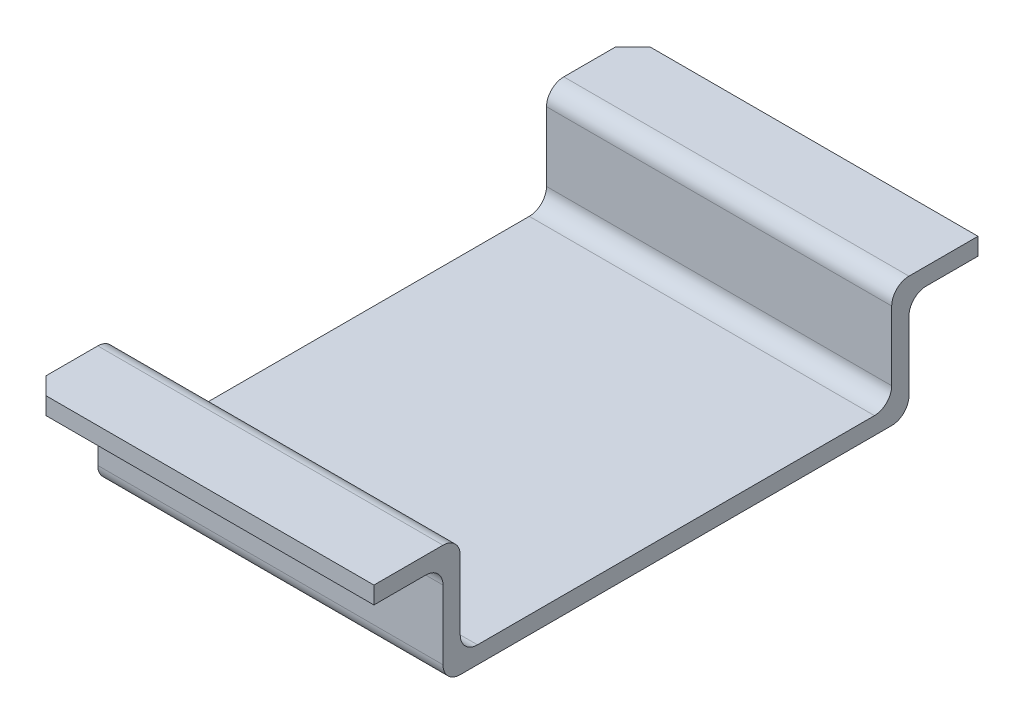
SolidWorks part; units mm, degrees
ref_plane "前视基准面" through (0, 0, 0) normal (0, 0, 1) x (1, 0, 0)
ref_plane "上视基准面" through (0, 0, 0) normal (0, 1, 0) x (1, 0, 0)
ref_plane "右视基准面" through (0, 0, 0) normal (1, 0, 0) x (0, 0, -1)
sketch "草图1" plane through (0, 0, 0) normal (1, 0, 0) x (0, 0, -1)
  line L0 (0, 0) -> (0, 32.2429) construction
  line L1 (0, 0) -> (-12.5, 0)
  line L2 (-12.5, 0) -> (-12.5, 6)
  line L3 (-12.5, 6) -> (-17.5, 6)
  line L4 (0, -1) -> (-13.5, -1)
  line L5 (-13.5, -1) -> (-13.5, 5)
  line L6 (-13.5, 5) -> (-17.5, 5)
  line L7 (0, -1) -> (13.5, -1)
  line L8 (-17.5, 6) -> (-17.5, 5)
  line L9 (0, 0) -> (12.5, 0)
  line L10 (13.5, -1) -> (13.5, 5)
  line L11 (12.5, 0) -> (12.5, 6)
  line L12 (13.5, 5) -> (17.5, 5)
  line L13 (17.5, 6) -> (17.5, 5)
  line L14 (12.5, 6) -> (17.5, 6)
  dimension "D2" = 12.5
  dimension "D3" = 6
  dimension "D4" = 17.5
  dimension "D1" = 1
extrude "凸台-拉伸1" add sketch "草图1" along normal blind 20
fillet "圆角1" radius 1 8 edges at (10, 6, 12.5) (10, 0, 12.5) (10, 5, 13.5) (10, -1, 13.5) (10, -1, -13.5) (10, 5, -13.5) (10, 6, -12.5) (10, 0, -12.5)
chamfer "倒角1" distance 1 angle 45 2 edges at (0, 5.5, 17.5) (0, 5.5, -17.5)
sketch "草图2" [suppressed] plane through (20, 0, 0) normal (1, 0, 0) x (0, 0, -1)
  line L12 (-12.5, 1) -> (-12.5, 5)
  line L13 (-13.5, 6) -> (-17.5, 6)
  line L14 (-17.5, 6) -> (-17.5, 5)
  line L15 (-17.5, 5) -> (-14.5, 5)
  line L16 (-13.5, 4) -> (-13.5, 0)
  line L17 (-12.5, -1) -> (12.5, -1)
  line L18 (13.5, 0) -> (13.5, 4)
  line L19 (14.5, 5) -> (17.5, 5)
  line L20 (17.5, 5) -> (17.5, 6)
  line L21 (17.5, 6) -> (13.5, 6)
  line L22 (12.5, 5) -> (12.5, 1)
  line L23 (11.5, 0) -> (-11.5, 0)
  line L24 (-12.5, 1) -> (-12.5, 5)
  line L25 (-13.5, 6) -> (-17.5, 6)
  line L26 (-17.5, 6) -> (-17.5, 5)
  line L27 (-17.5, 5) -> (-14.5, 5)
  line L28 (-13.5, 4) -> (-13.5, 0)
  line L29 (-12.5, -1) -> (12.5, -1)
  line L30 (13.5, 0) -> (13.5, 4)
  line L31 (14.5, 5) -> (17.5, 5)
  line L32 (17.5, 5) -> (17.5, 6)
  line L33 (17.5, 6) -> (13.5, 6)
  line L34 (12.5, 5) -> (12.5, 1)
  line L35 (11.5, 0) -> (-11.5, 0)
  arc A8 (-12.5, 5) -> (-13.5, 6) centre (-13.5, 5) ccw
  arc A9 (-13.5, 4) -> (-14.5, 5) centre (-14.5, 4) ccw
  arc A10 (-13.5, 0) -> (-12.5, -1) centre (-12.5, 0) ccw
  arc A11 (12.5, -1) -> (13.5, 0) centre (12.5, 0) ccw
  arc A12 (14.5, 5) -> (13.5, 4) centre (14.5, 4) ccw
  arc A13 (13.5, 6) -> (12.5, 5) centre (13.5, 5) ccw
  arc A14 (11.5, 0) -> (12.5, 1) centre (11.5, 1) ccw
  arc A15 (-12.5, 1) -> (-11.5, 0) centre (-11.5, 1) ccw
  arc A16 (-12.5, 5) -> (-13.5, 6) centre (-13.5, 5) ccw
  arc A17 (-13.5, 4) -> (-14.5, 5) centre (-14.5, 4) ccw
  arc A18 (-13.5, 0) -> (-12.5, -1) centre (-12.5, 0) ccw
  arc A19 (12.5, -1) -> (13.5, 0) centre (12.5, 0) ccw
  arc A20 (14.5, 5) -> (13.5, 4) centre (14.5, 4) ccw
  arc A21 (13.5, 6) -> (12.5, 5) centre (13.5, 5) ccw
  arc A22 (11.5, 0) -> (12.5, 1) centre (11.5, 1) ccw
  arc A23 (-12.5, 1) -> (-11.5, 0) centre (-11.5, 1) ccw
  dimension "D1" = 0
extrude "凸台-拉伸2" [suppressed] add sketch "草图2" along normal blind 30
chamfer "倒角2" [suppressed] distance 1 angle 45
sketch "草图3" [suppressed] plane through (0, 0, 0) normal (0, 1, 0) x (1, 0, 0)
  line L0 (5, 0) -> (13.6, 0) construction
  line L1 (5, 2.2) -> (13.6, 2.2)
  line L2 (5, -2.2) -> (13.6, -2.2)
  line L3 (25, 12.5) -> (25, -11.5) construction
  line L4 (0, 12.5) -> (50, 12.5) construction
  line L5 (0, -11.5) -> (50, -11.5) construction
  line L6 (0, 11.5) -> (0, -11.5) construction
  line L7 (45, 0) -> (36.4, 0) construction
  line L8 (45, 2.2) -> (36.4, 2.2)
  line L9 (45, -2.2) -> (36.4, -2.2)
  arc A0 (5, 2.2) -> (5, -2.2) centre (5, 0) ccw
  arc A1 (13.6, -2.2) -> (13.6, 2.2) centre (13.6, 0) ccw
  arc A2 (45, 2.2) -> (45, -2.2) centre (45, 0) cw
  arc A3 (36.4, -2.2) -> (36.4, 2.2) centre (36.4, 0) cw
  point P3 (9.3, 0)
  point P14 (2.8, 0)
  point P15 (15.8, 0)
  point P20 (40.7, 0)
  dimension "D3" = 2.2
  dimension "D1" = 13
  dimension "D2" = 5
extrude "切除-拉伸1" [suppressed] cut sketch "草图3" against normal blind 30
